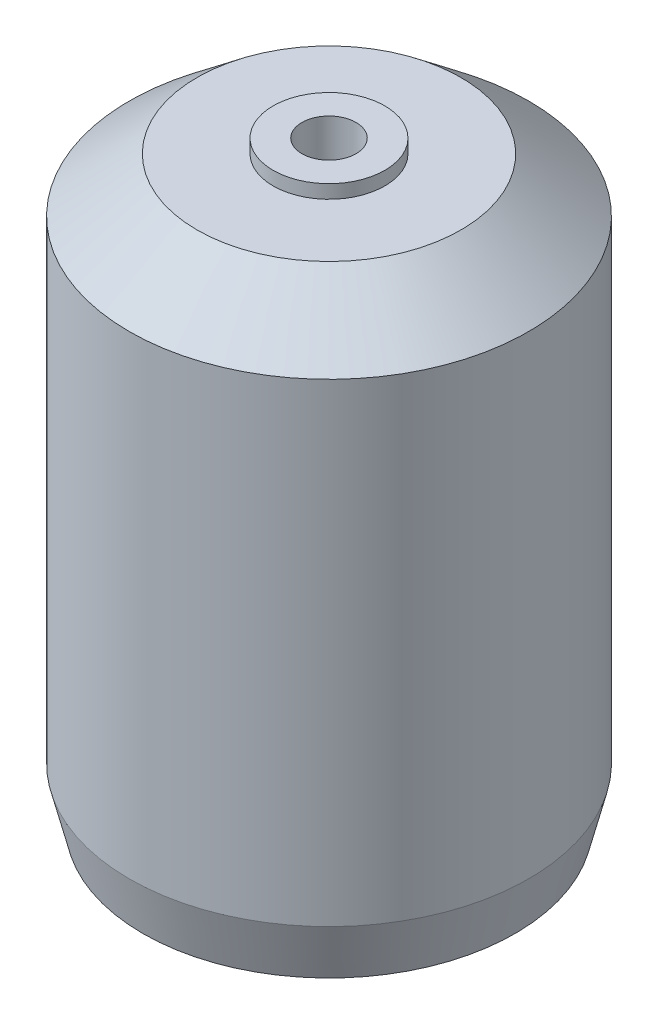
SolidWorks part; units mm, degrees
ref_plane "Front Plane" through (0, 0, 0) normal (0, 0, 1) x (1, 0, 0)
ref_plane "Top Plane" through (0, 0, 0) normal (0, 1, 0) x (1, 0, 0)
ref_plane "Right Plane" through (0, 0, 0) normal (1, 0, 0) x (0, 0, -1)
sketch "Sketch1" plane through (0, 0, 0) normal (0, 1, 0) x (1, 0, 0)
  circle A0 centre (0, 0) radius 29.5
extrude "Boss-Extrude1" add sketch "Sketch1" along normal blind 86
chamfer "Chamfer1" distance 8 distance2 10 1 edges at (0, 86, 29.5)
chamfer "Chamfer2" distance 2 distance2 8 1 edges at (0, 0, 29.5)
sketch "Sketch3" plane through (0, 86, 0) normal (0, 1, 0) x (1, 0, 0)
  circle A0 centre (0, 0) radius 8.25
  dimension "D1" = 16.5
extrude "Boss-Extrude2" add sketch "Sketch3" along normal blind 2
sketch "Sketch2" plane through (0, 0, 0) normal (0, -1, 0) x (1, 0, 0)
  circle A0 centre (0, 0) radius 4
extrude "Cut-Extrude1" cut sketch "Sketch2" against normal through all
